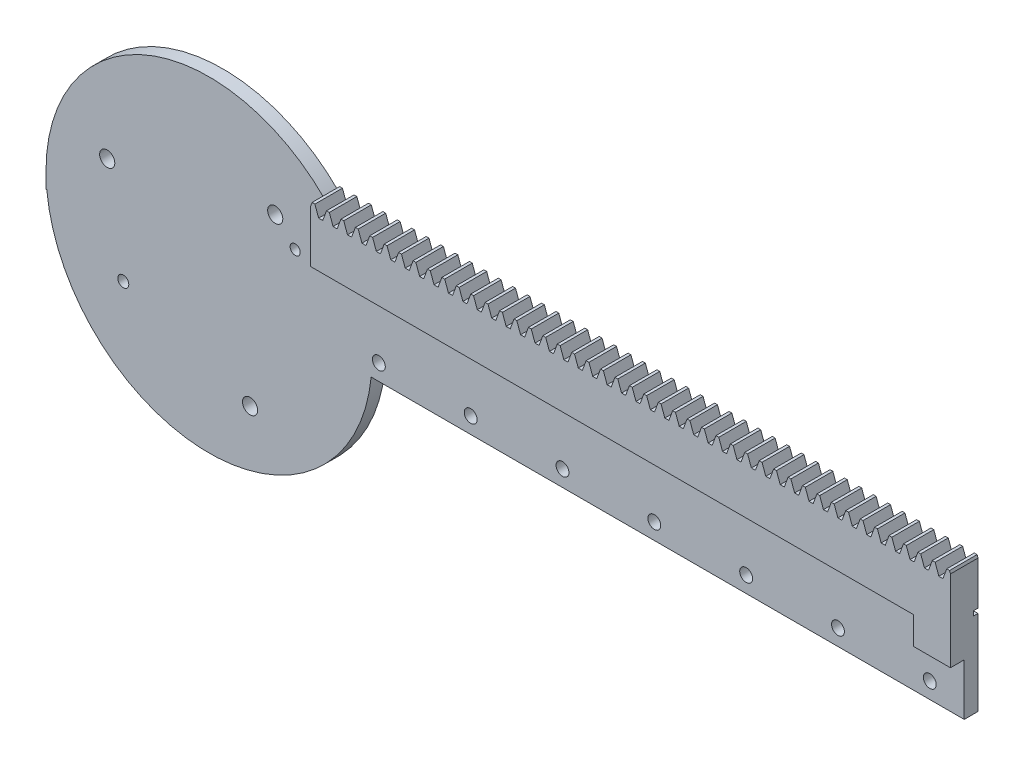
SolidWorks part; units mm, degrees
extrude "Blank" add sketch "BlankSke" against normal blind 3
sketch "BlankSke" plane through (0, 0, 0) normal (0, 0, 1) x (1, 0, 0)
  line L1 (0, 0) -> (200, 0)
  line L2 (0, 0) -> (0, 11)
  line L3 (0, 11) -> (200, 11)
  line L4 (200, 0) -> (200, 11)
  dimension "Length" = 200
  dimension "Blank_height" = 11
ref_plane "Plane1" through (0, 0, 0) normal (0, 0, 1) x (1, 0, 0)
ref_plane "Plane2" through (0, 0, 0) normal (0, 1, 0) x (1, 0, 0)
ref_plane "Plane3" through (0, 0, 0) normal (1, 0, 0) x (0, 0, -1)
other "Configuration Table"
sketch "HoldingSke" plane through (0, 0, 0) normal (0, 1, 0) x (1, 0, 0)
  line L0 (0, 0) -> (0.1392, 0.9903)
  line L1 (-15, 0) -> (100, 0) construction
  line L2 (0, 0) -> (-2.1039, 2.3779)
  line L3 (0, 0) -> (-11.863, 4.5341)
  line L4 (0, 0) -> (3.6497, 7.8269)
  line L5 (0, 0) -> (-23.7986, -8.8762)
  line L6 (0, 0) -> (-10.5278, -7.1032)
  line L9 (-71.009, 38.7566) -> (116.9296, 107.1606)
  line L10 (-76.2, 3.3779) -> (-66.2, 3.3779)
  line L11 (0, 0) -> (-3, 0)
  line L12 (-76.2, 101.6) -> (-76.162, 101.6)
  line L13 (24.9733, 27.94) -> (52.9518, 28.4284)
  line L14 (24.9733, 27.94) -> (24.9743, 27.94)
  line L15 (24.9733, 27.94) -> (100.4006, 29.5858)
  circle A0 centre (0, 0) radius 19.05
  circle A1 centre (0, 0) radius 5
  circle A2 centre (0, 0) radius 12.7
  dimension "MPH" = 10
  dimension "Diameter" = 38.1
  dimension "Num_teeth" = 65
  dimension "Pitch" = 1
  dimension "Show_teeth" = 998
  dimension "Thickness" = 12.7
  dimension "Ap" = 20
  dimension "Pitch_height" = 10
  dimension "Width" = 3
  dimension "Backlash" = 0.038
  dimension "Addendum_fac" = 1
  dimension "Dedendum_fac" = 1.25
  dimension "Clearance_fac" = 0.25
  dimension "Dedendum_add" = 0.001
  dimension "Length" = 200
  dimension "Module" = 1
sketch "TooCutSkeIll" plane through (0, 0, 0) normal (0, 0, 1) x (1, 0, 0)
  line L0 (-1.2538, 10.9737) -> (-0.5045, 8.9152)
  line L1 (-0.2687, 8.75) -> (0.2687, 8.75)
  line L2 (0.5045, 8.9152) -> (1.2538, 10.9737)
  line L3 (200, 11) -> (0, 11) construction
  line L4 (0, 0) -> (0, 64.897) construction
  line L5 (-13.208, 10) -> (12.954, 10) construction
  line L6 (0, 0) -> (200, 0) construction
  line L7 (0.8994, 10) -> (0.8994, 48.7463) construction
  line L8 (-0.8994, 10) -> (-0.8994, 48.7463) construction
  line L9 (1.2914, 11) -> (1.2914, 11.0254)
  line L10 (-1.2914, 11) -> (-1.2914, 11.0254)
  line L11 (-1.2914, 11.0254) -> (1.2914, 11.0254)
  arc A0 (0.2687, 8.75) -> (0.5045, 8.9152) centre (0.2687, 9.001) ccw
  arc A1 (-0.5045, 8.9152) -> (-0.2687, 8.75) centre (-0.2687, 9.001) ccw
  arc A2 (1.2914, 11) -> (1.2538, 10.9737) centre (1.2914, 10.96) ccw
  arc A3 (-1.2538, 10.9737) -> (-1.2914, 11) centre (-1.2914, 10.96) ccw
  dimension "Pitch_height" = 10
  dimension "Addendum_plus" = 1.0254
  dimension "Pressure_angle" = 20
  dimension "Gap_width" = 1.7988
  dimension "Dedendum" = 1.25
extrude "ToothCutIll" [suppressed] cut sketch "TooCutSkeIll" against normal through all
sketch "TooCutSkeSim" plane through (0, 0, 0) normal (0, 0, 1) x (1, 0, 0)
  line L0 (0.4444, 8.75) -> (-0.4444, 8.75)
  line L1 (1.2726, 11.0254) -> (0.4444, 8.75)
  line L2 (0, 17.4625) -> (0, 53.467) construction
  line L3 (1.2726, 11.0254) -> (-1.2726, 11.0254)
  line L6 (-1.2726, 11.0254) -> (-0.4444, 8.75)
  line L9 (-0.8994, 10) -> (0.8994, 10) construction
  line L10 (0, 0) -> (200, 0) construction
  line L11 (0.8994, 10) -> (0.8994, 53.467) construction
  line L12 (-0.8994, 10) -> (-0.8994, 53.467) construction
  dimension "Pitch_height" = 10
  dimension "Addendum_plus" = 1.0254
  dimension "Pressure_angle" = 20
  dimension "Gap_width" = 1.7988
  dimension "Dedendum" = 1.25
extrude "ToothCutSim" cut sketch "TooCutSkeSim" against normal through all
pattern_linear "TeethCuts" count 64 spacing 3.1416 along (1, 0, 0) of "ToothCutIll", "ToothCutSim"
sketch "草图5" plane through (0, 0, 0) normal (0, -1, 0) x (1, 0, 0)
  line L4 (200, 0) -> (0, 0)
  line L5 (0, 0) -> (0, -3)
  line L6 (0, -3) -> (200, -3)
  line L7 (200, -3) -> (200, 0)
  line L8 (200, 0) -> (0, 0)
  line L9 (0, 0) -> (0, -3)
  line L10 (0, -3) -> (200, -3)
  line L11 (200, -3) -> (200, 0)
  dimension "D1" = 0
extrude "凸台-拉伸3" add sketch "草图5" along normal blind 18.5
sketch "草图6" plane through (0, 0, -3) normal (0, 0, -1) x (-1, 0, 0)
  line L0 (0, 8.75) -> (0, -18.5) construction
  line L1 (0, -18.5) -> (-200, -18.5) construction
  circle A0 centre (-35.5, -15) radius 35.5
  dimension "D1" = 71
  dimension "D2" = 3.5
extrude "凸台-拉伸4" add sketch "草图6" against normal blind 3
sketch "草图7" plane through (0, 0, 0) normal (0, 0, 1) x (1, 0, 0)
  line L0 (200, 10.4466) -> (200, -1.25)
  line L1 (200, -18.5) -> (200, 10.4466) construction
  line L2 (200, -1.25) -> (60.6203, -1.25)
  line L5 (60.6203, 10.0842) -> (60.6203, -1.25)
  line L204 (70.827, -18.5) -> (200, -18.5)
  line L259 (200, -18.5) -> (200, 10.4466)
  line L260 (200, 10.4466) -> (199.7986, 11)
  line L261 (199.7986, 11) -> (199.1837, 11)
  line L262 (199.1837, 11) -> (198.3648, 8.75)
  line L263 (198.3648, 8.75) -> (197.4759, 8.75)
  line L264 (197.4759, 8.75) -> (196.657, 11)
  line L265 (196.657, 11) -> (196.0421, 11)
  line L266 (196.0421, 11) -> (195.2232, 8.75)
  line L267 (195.2232, 8.75) -> (194.3343, 8.75)
  line L268 (194.3343, 8.75) -> (193.5154, 11)
  line L269 (193.5154, 11) -> (192.9005, 11)
  line L270 (192.9005, 11) -> (192.0816, 8.75)
  line L271 (192.0816, 8.75) -> (191.1927, 8.75)
  line L272 (191.1927, 8.75) -> (190.3738, 11)
  line L273 (190.3738, 11) -> (189.7589, 11)
  line L274 (189.7589, 11) -> (188.94, 8.75)
  line L275 (188.94, 8.75) -> (188.0511, 8.75)
  line L276 (188.0511, 8.75) -> (187.2322, 11)
  line L277 (187.2322, 11) -> (186.6173, 11)
  line L278 (186.6173, 11) -> (185.7984, 8.75)
  line L279 (185.7984, 8.75) -> (184.9095, 8.75)
  line L280 (184.9095, 8.75) -> (184.0906, 11)
  line L281 (184.0906, 11) -> (183.4757, 11)
  line L282 (183.4757, 11) -> (182.6568, 8.75)
  line L283 (182.6568, 8.75) -> (181.7679, 8.75)
  line L284 (181.7679, 8.75) -> (180.949, 11)
  line L285 (180.949, 11) -> (180.3341, 11)
  line L286 (180.3341, 11) -> (179.5152, 8.75)
  line L287 (179.5152, 8.75) -> (178.6263, 8.75)
  line L288 (178.6263, 8.75) -> (177.8074, 11)
  line L289 (177.8074, 11) -> (177.1926, 11)
  line L290 (177.1926, 11) -> (176.3736, 8.75)
  line L291 (176.3736, 8.75) -> (175.4848, 8.75)
  line L292 (175.4848, 8.75) -> (174.6658, 11)
  line L293 (174.6658, 11) -> (174.051, 11)
  line L294 (174.051, 11) -> (173.232, 8.75)
  line L295 (173.232, 8.75) -> (172.3432, 8.75)
  line L296 (172.3432, 8.75) -> (171.5242, 11)
  line L297 (171.5242, 11) -> (170.9094, 11)
  line L298 (170.9094, 11) -> (170.0904, 8.75)
  line L299 (170.0904, 8.75) -> (169.2016, 8.75)
  line L300 (169.2016, 8.75) -> (168.3826, 11)
  line L301 (168.3826, 11) -> (167.7678, 11)
  line L302 (167.7678, 11) -> (166.9488, 8.75)
  line L303 (166.9488, 8.75) -> (166.06, 8.75)
  line L304 (166.06, 8.75) -> (165.241, 11)
  line L305 (165.241, 11) -> (164.6262, 11)
  line L306 (164.6262, 11) -> (163.8073, 8.75)
  line L307 (163.8073, 8.75) -> (162.9184, 8.75)
  line L308 (162.9184, 8.75) -> (162.0994, 11)
  line L309 (162.0994, 11) -> (161.4846, 11)
  line L310 (161.4846, 11) -> (160.6657, 8.75)
  line L311 (160.6657, 8.75) -> (159.7768, 8.75)
  line L312 (159.7768, 8.75) -> (158.9579, 11)
  line L313 (158.9579, 11) -> (158.343, 11)
  line L314 (158.343, 11) -> (157.5241, 8.75)
  line L315 (157.5241, 8.75) -> (156.6352, 8.75)
  line L316 (156.6352, 8.75) -> (155.8163, 11)
  line L317 (155.8163, 11) -> (155.2014, 11)
  line L318 (155.2014, 11) -> (154.3825, 8.75)
  line L319 (154.3825, 8.75) -> (153.4936, 8.75)
  line L320 (153.4936, 8.75) -> (152.6747, 11)
  line L321 (152.6747, 11) -> (152.0598, 11)
  line L322 (152.0598, 11) -> (151.2409, 8.75)
  line L323 (151.2409, 8.75) -> (150.352, 8.75)
  line L324 (150.352, 8.75) -> (149.5331, 11)
  line L325 (149.5331, 11) -> (148.9182, 11)
  line L326 (148.9182, 11) -> (148.0993, 8.75)
  line L327 (148.0993, 8.75) -> (147.2104, 8.75)
  line L328 (147.2104, 8.75) -> (146.3915, 11)
  line L329 (146.3915, 11) -> (145.7766, 11)
  line L330 (145.7766, 11) -> (144.9577, 8.75)
  line L331 (144.9577, 8.75) -> (144.0688, 8.75)
  line L332 (144.0688, 8.75) -> (143.2499, 11)
  line L333 (143.2499, 11) -> (142.635, 11)
  line L334 (142.635, 11) -> (141.8161, 8.75)
  line L335 (141.8161, 8.75) -> (140.9272, 8.75)
  line L336 (140.9272, 8.75) -> (140.1083, 11)
  line L337 (140.1083, 11) -> (139.4934, 11)
  line L338 (139.4934, 11) -> (138.6745, 8.75)
  line L339 (138.6745, 8.75) -> (137.7856, 8.75)
  line L340 (137.7856, 8.75) -> (136.9667, 11)
  line L341 (136.9667, 11) -> (136.3519, 11)
  line L342 (136.3519, 11) -> (135.5329, 8.75)
  line L343 (135.5329, 8.75) -> (134.644, 8.75)
  line L344 (134.644, 8.75) -> (133.8251, 11)
  line L345 (133.8251, 11) -> (133.2103, 11)
  line L346 (133.2103, 11) -> (132.3913, 8.75)
  line L347 (132.3913, 8.75) -> (131.5025, 8.75)
  line L348 (131.5025, 8.75) -> (130.6835, 11)
  line L349 (130.6835, 11) -> (130.0687, 11)
  line L350 (130.0687, 11) -> (129.2497, 8.75)
  line L351 (129.2497, 8.75) -> (128.3609, 8.75)
  line L352 (128.3609, 8.75) -> (127.5419, 11)
  line L353 (127.5419, 11) -> (126.9271, 11)
  line L354 (126.9271, 11) -> (126.1081, 8.75)
  line L355 (126.1081, 8.75) -> (125.2193, 8.75)
  line L356 (125.2193, 8.75) -> (124.4003, 11)
  line L357 (124.4003, 11) -> (123.7855, 11)
  line L358 (123.7855, 11) -> (122.9665, 8.75)
  line L359 (122.9665, 8.75) -> (122.0777, 8.75)
  line L360 (122.0777, 8.75) -> (121.2587, 11)
  line L361 (121.2587, 11) -> (120.6439, 11)
  line L362 (120.6439, 11) -> (119.825, 8.75)
  line L363 (119.825, 8.75) -> (118.9361, 8.75)
  line L364 (118.9361, 8.75) -> (118.1172, 11)
  line L365 (118.1172, 11) -> (117.5023, 11)
  line L366 (117.5023, 11) -> (116.6834, 8.75)
  line L367 (116.6834, 8.75) -> (115.7945, 8.75)
  line L368 (115.7945, 8.75) -> (114.9756, 11)
  line L369 (114.9756, 11) -> (114.3607, 11)
  line L370 (114.3607, 11) -> (113.5418, 8.75)
  line L371 (113.5418, 8.75) -> (112.6529, 8.75)
  line L372 (112.6529, 8.75) -> (111.834, 11)
  line L373 (111.834, 11) -> (111.2191, 11)
  line L374 (111.2191, 11) -> (110.4002, 8.75)
  line L375 (110.4002, 8.75) -> (109.5113, 8.75)
  line L376 (109.5113, 8.75) -> (108.6924, 11)
  line L377 (108.6924, 11) -> (108.0775, 11)
  line L378 (108.0775, 11) -> (107.2586, 8.75)
  line L379 (107.2586, 8.75) -> (106.3697, 8.75)
  line L380 (106.3697, 8.75) -> (105.5508, 11)
  line L381 (105.5508, 11) -> (104.9359, 11)
  line L382 (104.9359, 11) -> (104.117, 8.75)
  line L383 (104.117, 8.75) -> (103.2281, 8.75)
  line L384 (103.2281, 8.75) -> (102.4092, 11)
  line L385 (102.4092, 11) -> (101.7943, 11)
  line L386 (101.7943, 11) -> (100.9754, 8.75)
  line L387 (100.9754, 8.75) -> (100.0865, 8.75)
  line L388 (100.0865, 8.75) -> (99.2676, 11)
  line L389 (99.2676, 11) -> (98.6527, 11)
  line L390 (98.6527, 11) -> (97.8338, 8.75)
  line L391 (97.8338, 8.75) -> (96.9449, 8.75)
  line L392 (96.9449, 8.75) -> (96.126, 11)
  line L393 (96.126, 11) -> (95.5111, 11)
  line L394 (95.5111, 11) -> (94.6922, 8.75)
  line L395 (94.6922, 8.75) -> (93.8033, 8.75)
  line L396 (93.8033, 8.75) -> (92.9844, 11)
  line L397 (92.9844, 11) -> (92.3696, 11)
  line L398 (92.3696, 11) -> (91.5506, 8.75)
  line L399 (91.5506, 8.75) -> (90.6618, 8.75)
  line L400 (90.6618, 8.75) -> (89.8428, 11)
  line L401 (89.8428, 11) -> (89.228, 11)
  line L402 (89.228, 11) -> (88.409, 8.75)
  line L403 (88.409, 8.75) -> (87.5202, 8.75)
  line L404 (87.5202, 8.75) -> (86.7012, 11)
  line L405 (86.7012, 11) -> (86.0864, 11)
  line L406 (86.0864, 11) -> (85.2674, 8.75)
  line L407 (85.2674, 8.75) -> (84.3786, 8.75)
  line L408 (84.3786, 8.75) -> (83.5596, 11)
  line L409 (83.5596, 11) -> (82.9448, 11)
  line L410 (82.9448, 11) -> (82.1258, 8.75)
  line L411 (82.1258, 8.75) -> (81.237, 8.75)
  line L412 (81.237, 8.75) -> (80.418, 11)
  line L413 (80.418, 11) -> (79.8032, 11)
  line L414 (79.8032, 11) -> (78.9843, 8.75)
  line L415 (78.9843, 8.75) -> (78.0954, 8.75)
  line L416 (78.0954, 8.75) -> (77.2764, 11)
  line L417 (77.2764, 11) -> (76.6616, 11)
  line L418 (76.6616, 11) -> (75.8427, 8.75)
  line L419 (75.8427, 8.75) -> (74.9538, 8.75)
  line L420 (74.9538, 8.75) -> (74.1349, 11)
  line L421 (74.1349, 11) -> (73.52, 11)
  line L422 (73.52, 11) -> (72.7011, 8.75)
  line L423 (72.7011, 8.75) -> (71.8122, 8.75)
  line L424 (71.8122, 8.75) -> (70.9933, 11)
  line L425 (70.9933, 11) -> (70.3784, 11)
  line L426 (70.3784, 11) -> (69.5595, 8.75)
  line L427 (69.5595, 8.75) -> (68.6706, 8.75)
  line L428 (68.6706, 8.75) -> (67.8517, 11)
  line L429 (67.8517, 11) -> (67.2368, 11)
  line L430 (67.2368, 11) -> (66.4179, 8.75)
  line L431 (66.4179, 8.75) -> (65.529, 8.75)
  line L432 (65.529, 8.75) -> (64.7101, 11)
  line L433 (64.7101, 11) -> (64.0952, 11)
  line L434 (64.0952, 11) -> (63.2763, 8.75)
  line L435 (63.2763, 8.75) -> (62.3874, 8.75)
  line L436 (62.3874, 8.75) -> (61.5685, 11)
  line L437 (61.5685, 11) -> (60.9536, 11)
  line L438 (60.9536, 11) -> (60.6203, 10.0842)
  line L500 (11.3095, 10.9821) -> (11.303, 11)
  line L501 (11.303, 11) -> (10.6881, 11)
  line L502 (10.6881, 11) -> (10.3406, 10.045)
  line L503 (9.1146, 8.75) -> (8.9803, 8.75)
  line L504 (8.9803, 8.75) -> (8.1614, 11)
  line L505 (8.1614, 11) -> (7.5466, 11)
  line L506 (7.5466, 11) -> (6.7276, 8.75)
  line L507 (6.7276, 8.75) -> (5.8387, 8.75)
  line L508 (5.8387, 8.75) -> (5.0198, 11)
  line L509 (5.0198, 11) -> (4.405, 11)
  line L510 (4.405, 11) -> (3.586, 8.75)
  line L511 (3.586, 8.75) -> (2.6972, 8.75)
  line L512 (2.6972, 8.75) -> (1.8782, 11)
  line L513 (1.8782, 11) -> (1.2634, 11)
  line L514 (1.2634, 11) -> (0.4444, 8.75)
  line L515 (0.4444, 8.75) -> (0, 8.75)
  line L516 (0, 8.75) -> (0, -18.5)
  line L517 (0, -18.5) -> (0.173, -18.5)
  line L519 (200, 10.4466) -> (199.7986, 11)
  line L520 (199.7986, 11) -> (199.1837, 11)
  line L521 (199.1837, 11) -> (198.3648, 8.75)
  line L522 (198.3648, 8.75) -> (197.4759, 8.75)
  line L523 (197.4759, 8.75) -> (196.657, 11)
  line L524 (196.657, 11) -> (196.0421, 11)
  line L525 (196.0421, 11) -> (195.2232, 8.75)
  line L526 (195.2232, 8.75) -> (194.3343, 8.75)
  line L527 (194.3343, 8.75) -> (193.5154, 11)
  line L528 (193.5154, 11) -> (192.9005, 11)
  line L529 (192.9005, 11) -> (192.0816, 8.75)
  line L530 (192.0816, 8.75) -> (191.1927, 8.75)
  line L531 (191.1927, 8.75) -> (190.3738, 11)
  line L532 (190.3738, 11) -> (189.7589, 11)
  line L533 (189.7589, 11) -> (188.94, 8.75)
  line L534 (188.94, 8.75) -> (188.0511, 8.75)
  line L535 (188.0511, 8.75) -> (187.2322, 11)
  line L536 (187.2322, 11) -> (186.6173, 11)
  line L537 (186.6173, 11) -> (185.7984, 8.75)
  line L538 (185.7984, 8.75) -> (184.9095, 8.75)
  line L539 (184.9095, 8.75) -> (184.0906, 11)
  line L540 (184.0906, 11) -> (183.4757, 11)
  line L541 (183.4757, 11) -> (182.6568, 8.75)
  line L542 (182.6568, 8.75) -> (181.7679, 8.75)
  line L543 (181.7679, 8.75) -> (180.949, 11)
  line L544 (180.949, 11) -> (180.3341, 11)
  line L545 (180.3341, 11) -> (179.5152, 8.75)
  line L546 (179.5152, 8.75) -> (178.6263, 8.75)
  line L547 (178.6263, 8.75) -> (177.8074, 11)
  line L548 (177.8074, 11) -> (177.1926, 11)
  line L549 (177.1926, 11) -> (176.3736, 8.75)
  line L550 (176.3736, 8.75) -> (175.4848, 8.75)
  line L551 (175.4848, 8.75) -> (174.6658, 11)
  line L552 (174.6658, 11) -> (174.051, 11)
  line L553 (174.051, 11) -> (173.232, 8.75)
  line L554 (173.232, 8.75) -> (172.3432, 8.75)
  line L555 (172.3432, 8.75) -> (171.5242, 11)
  line L556 (171.5242, 11) -> (170.9094, 11)
  line L557 (170.9094, 11) -> (170.0904, 8.75)
  line L558 (170.0904, 8.75) -> (169.2016, 8.75)
  line L559 (169.2016, 8.75) -> (168.3826, 11)
  line L560 (168.3826, 11) -> (167.7678, 11)
  line L561 (167.7678, 11) -> (166.9488, 8.75)
  line L562 (166.9488, 8.75) -> (166.06, 8.75)
  line L563 (166.06, 8.75) -> (165.241, 11)
  line L564 (165.241, 11) -> (164.6262, 11)
  line L565 (164.6262, 11) -> (163.8073, 8.75)
  line L566 (163.8073, 8.75) -> (162.9184, 8.75)
  line L567 (162.9184, 8.75) -> (162.0994, 11)
  line L568 (162.0994, 11) -> (161.4846, 11)
  line L569 (161.4846, 11) -> (160.6657, 8.75)
  line L570 (160.6657, 8.75) -> (159.7768, 8.75)
  line L571 (159.7768, 8.75) -> (158.9579, 11)
  line L572 (158.9579, 11) -> (158.343, 11)
  line L573 (158.343, 11) -> (157.5241, 8.75)
  line L574 (157.5241, 8.75) -> (156.6352, 8.75)
  line L575 (156.6352, 8.75) -> (155.8163, 11)
  line L576 (155.8163, 11) -> (155.2014, 11)
  line L577 (155.2014, 11) -> (154.3825, 8.75)
  line L578 (154.3825, 8.75) -> (153.4936, 8.75)
  line L579 (153.4936, 8.75) -> (152.6747, 11)
  line L580 (152.6747, 11) -> (152.0598, 11)
  line L581 (152.0598, 11) -> (151.2409, 8.75)
  line L582 (151.2409, 8.75) -> (150.352, 8.75)
  line L583 (150.352, 8.75) -> (149.5331, 11)
  line L584 (149.5331, 11) -> (148.9182, 11)
  line L585 (148.9182, 11) -> (148.0993, 8.75)
  line L586 (148.0993, 8.75) -> (147.2104, 8.75)
  line L587 (147.2104, 8.75) -> (146.3915, 11)
  line L588 (146.3915, 11) -> (145.7766, 11)
  line L589 (145.7766, 11) -> (144.9577, 8.75)
  line L590 (144.9577, 8.75) -> (144.0688, 8.75)
  line L591 (144.0688, 8.75) -> (143.2499, 11)
  line L592 (143.2499, 11) -> (142.635, 11)
  line L593 (142.635, 11) -> (141.8161, 8.75)
  line L594 (141.8161, 8.75) -> (140.9272, 8.75)
  line L595 (140.9272, 8.75) -> (140.1083, 11)
  line L596 (140.1083, 11) -> (139.4934, 11)
  line L597 (139.4934, 11) -> (138.6745, 8.75)
  line L598 (138.6745, 8.75) -> (137.7856, 8.75)
  line L599 (137.7856, 8.75) -> (136.9667, 11)
  line L600 (136.9667, 11) -> (136.3519, 11)
  line L601 (136.3519, 11) -> (135.5329, 8.75)
  line L602 (135.5329, 8.75) -> (134.644, 8.75)
  line L603 (134.644, 8.75) -> (133.8251, 11)
  line L604 (133.8251, 11) -> (133.2103, 11)
  line L605 (133.2103, 11) -> (132.3913, 8.75)
  line L606 (132.3913, 8.75) -> (131.5025, 8.75)
  line L607 (131.5025, 8.75) -> (130.6835, 11)
  line L608 (130.6835, 11) -> (130.0687, 11)
  line L609 (130.0687, 11) -> (129.2497, 8.75)
  line L610 (129.2497, 8.75) -> (128.3609, 8.75)
  line L611 (128.3609, 8.75) -> (127.5419, 11)
  line L612 (127.5419, 11) -> (126.9271, 11)
  line L613 (126.9271, 11) -> (126.1081, 8.75)
  line L614 (126.1081, 8.75) -> (125.2193, 8.75)
  line L615 (125.2193, 8.75) -> (124.4003, 11)
  line L616 (124.4003, 11) -> (123.7855, 11)
  line L617 (123.7855, 11) -> (122.9665, 8.75)
  line L618 (122.9665, 8.75) -> (122.0777, 8.75)
  line L619 (122.0777, 8.75) -> (121.2587, 11)
  line L620 (121.2587, 11) -> (120.6439, 11)
  line L621 (120.6439, 11) -> (119.825, 8.75)
  line L622 (119.825, 8.75) -> (118.9361, 8.75)
  line L623 (118.9361, 8.75) -> (118.1172, 11)
  line L624 (118.1172, 11) -> (117.5023, 11)
  line L625 (117.5023, 11) -> (116.6834, 8.75)
  line L626 (116.6834, 8.75) -> (115.7945, 8.75)
  line L627 (115.7945, 8.75) -> (114.9756, 11)
  line L628 (114.9756, 11) -> (114.3607, 11)
  line L629 (114.3607, 11) -> (113.5418, 8.75)
  line L630 (113.5418, 8.75) -> (112.6529, 8.75)
  line L631 (112.6529, 8.75) -> (111.834, 11)
  line L632 (111.834, 11) -> (111.2191, 11)
  line L633 (111.2191, 11) -> (110.4002, 8.75)
  line L634 (110.4002, 8.75) -> (109.5113, 8.75)
  line L635 (109.5113, 8.75) -> (108.6924, 11)
  line L636 (108.6924, 11) -> (108.0775, 11)
  line L637 (108.0775, 11) -> (107.2586, 8.75)
  line L638 (107.2586, 8.75) -> (106.3697, 8.75)
  line L639 (106.3697, 8.75) -> (105.5508, 11)
  line L640 (105.5508, 11) -> (104.9359, 11)
  line L641 (104.9359, 11) -> (104.117, 8.75)
  line L642 (104.117, 8.75) -> (103.2281, 8.75)
  line L643 (103.2281, 8.75) -> (102.4092, 11)
  line L644 (102.4092, 11) -> (101.7943, 11)
  line L645 (101.7943, 11) -> (100.9754, 8.75)
  line L646 (100.9754, 8.75) -> (100.0865, 8.75)
  line L647 (100.0865, 8.75) -> (99.2676, 11)
  line L648 (99.2676, 11) -> (98.6527, 11)
  line L649 (98.6527, 11) -> (97.8338, 8.75)
  line L650 (97.8338, 8.75) -> (96.9449, 8.75)
  line L651 (96.9449, 8.75) -> (96.126, 11)
  line L652 (96.126, 11) -> (95.5111, 11)
  line L653 (95.5111, 11) -> (94.6922, 8.75)
  line L654 (94.6922, 8.75) -> (93.8033, 8.75)
  line L655 (93.8033, 8.75) -> (92.9844, 11)
  line L656 (92.9844, 11) -> (92.3696, 11)
  line L657 (92.3696, 11) -> (91.5506, 8.75)
  line L658 (91.5506, 8.75) -> (90.6618, 8.75)
  line L659 (90.6618, 8.75) -> (89.8428, 11)
  line L660 (89.8428, 11) -> (89.228, 11)
  line L661 (89.228, 11) -> (88.409, 8.75)
  line L662 (88.409, 8.75) -> (87.5202, 8.75)
  line L663 (87.5202, 8.75) -> (86.7012, 11)
  line L664 (86.7012, 11) -> (86.0864, 11)
  line L665 (86.0864, 11) -> (85.2674, 8.75)
  line L666 (85.2674, 8.75) -> (84.3786, 8.75)
  line L667 (84.3786, 8.75) -> (83.5596, 11)
  line L668 (83.5596, 11) -> (82.9448, 11)
  line L669 (82.9448, 11) -> (82.1258, 8.75)
  line L670 (82.1258, 8.75) -> (81.237, 8.75)
  line L671 (81.237, 8.75) -> (80.418, 11)
  line L672 (80.418, 11) -> (79.8032, 11)
  line L673 (79.8032, 11) -> (78.9843, 8.75)
  line L674 (78.9843, 8.75) -> (78.0954, 8.75)
  line L675 (78.0954, 8.75) -> (77.2764, 11)
  line L676 (77.2764, 11) -> (76.6616, 11)
  line L677 (76.6616, 11) -> (75.8427, 8.75)
  line L678 (75.8427, 8.75) -> (74.9538, 8.75)
  line L679 (74.9538, 8.75) -> (74.1349, 11)
  line L680 (74.1349, 11) -> (73.52, 11)
  line L681 (73.52, 11) -> (72.7011, 8.75)
  line L682 (72.7011, 8.75) -> (71.8122, 8.75)
  line L683 (71.8122, 8.75) -> (70.9933, 11)
  line L684 (70.9933, 11) -> (70.3784, 11)
  line L685 (70.3784, 11) -> (69.5595, 8.75)
  line L686 (69.5595, 8.75) -> (68.6706, 8.75)
  line L687 (68.6706, 8.75) -> (67.8517, 11)
  line L688 (67.8517, 11) -> (67.2368, 11)
  line L689 (67.2368, 11) -> (66.4179, 8.75)
  line L690 (66.4179, 8.75) -> (65.529, 8.75)
  line L691 (65.529, 8.75) -> (64.7101, 11)
  line L692 (64.7101, 11) -> (64.0952, 11)
  line L693 (64.0952, 11) -> (63.2763, 8.75)
  line L694 (63.2763, 8.75) -> (62.3874, 8.75)
  line L695 (62.3874, 8.75) -> (61.5685, 11)
  line L696 (61.5685, 11) -> (60.9536, 11)
  line L697 (60.9536, 11) -> (60.6203, 10.0842)
  arc A3 (0.173, -18.5) -> (70.827, -18.5) centre (35.5, -15) ccw
  arc A5 (60.6203, 10.0842) -> (11.3095, 10.9821) centre (35.5, -15) ccw
  arc A7 (10.3406, 10.045) -> (9.1146, 8.75) centre (35.5, -15) ccw
  dimension "D1" = 0
extrude "凸台-拉伸6" add sketch "草图7" along normal blind 3
sketch "草图8" plane through (0, 0, 0) normal (0, 0, 1) x (1, 0, 0)
  line L0 (35.5, 20.5) -> (0, 20.5)
  line L2 (0, 8.75) -> (0, -18.5) construction
  line L3 (0, -15) -> (0, 20.5)
  arc A0 (35.5, 20.5) -> (0, -15) centre (35.5, -15) ccw
extrude "切除-拉伸1" cut sketch "草图8" against normal blind 3
sketch "草图9" plane through (0, 0, 0) normal (0, 0, 1) x (1, 0, 0)
  circle A0 centre (72.5, -15) radius 1.4
  circle A1 centre (92.5, -15) radius 1.4
  circle A2 centre (112.5, -15) radius 1.4
  circle A3 centre (132.5, -15) radius 1.4
  circle A4 centre (152.5, -15) radius 1.4
  circle A5 centre (172.5, -15) radius 1.4
  circle A6 centre (192.5, -15) radius 1.4
  dimension "D1" = 2.8
  dimension "D2" = 7
extrude "切除-拉伸2" cut sketch "草图9" against normal blind 10
sketch "草图11" plane through (0, 0, 0) normal (0, 0, 1) x (1, 0, 0)
  line L1 (200, -1.25) -> (192, -1.25)
  line L2 (200, -1.25) -> (200, -7.25)
  line L3 (200, -7.25) -> (192, -7.25)
  line L4 (192, -1.25) -> (192, -7.25)
  dimension "D1" = 8
  dimension "D2" = 6
extrude "凸台-拉伸7" add sketch "草图11" along normal blind 3
sketch "草图12" plane through (0, 0, -3) normal (0, 0, -1) x (-1, 0, 0)
  line L0 (-200, -18.5) -> (-200, 10.4466) construction
  line L1 (-200, 1) -> (-70.8357, 1)
  line L2 (-200, 1) -> (-200, 0)
  line L3 (-200, 0) -> (-70.8357, 0)
  line L4 (-70.8357, 1) -> (-70.8357, 0)
  dimension "D1" = 1
extrude "切除-拉伸3" cut sketch "草图12" against normal blind 1
sketch "草图13" plane through (0, 0, -3) normal (0, 0, -1) x (-1, 0, 0)
  circle A1 centre (-13.3322, -6.0551) radius 1.65
  circle A3 centre (-49.925, 1.6877) radius 1.65
  circle A4 centre (-44.4449, -37.1678) radius 1.65
  circle A6 centre (-54.2801, -2.7253) radius 1.1
  circle A7 centre (-16.8324, -27.4451) radius 1.2
  dimension "D1" = 2.2
  dimension "D2" = 3.3
  dimension "D4" = 3.3
  dimension "D5" = 3.3
extrude "切除-拉伸4" cut sketch "草图13" against normal through all
equation "' \"Module@HoldingSke\" = 6.35"
equation "' \"Num_teeth@HoldingSke\" = 12"
equation "' \"Ap@HoldingSke\" =  20"
equation "' \"Ap@HoldingSke\" = 20"
equation "' \"Width@HoldingSke\" = 0.25 * 25.4"
equation "' \"Show_teeth@HoldingSke\" = 500"
equation "' \"Backlash@HoldingSke\" = 0.009 * 25.4"
equation "' \"Addendum_fac@HoldingSke\" = 1.0"
equation "' \"Dedendum_fac@HoldingSke\" = 1.25"
equation "' \"Dedendum_add@HoldingSke\" = 0.00005 * 25.4"
equation "' \"Clearance_fac@HoldingSke\" = 0.25"
equation "' \"Pitch_height@HoldingSke\" = 1 * 25.4"
equation "' \"Length@HoldingSke\" = 4.71 * 25.4"
equation "\"Pitch@HoldingSke\" = 1 / \"Module@HoldingSke\""
equation "\"MPH@HoldingSke\" = \"Dedendum_fac@HoldingSke\" / \"Pitch@HoldingSke\" + 2 * \"Dedendum_add@HoldingSke\" + 0.002 * 25.4"
equation "\"MPH@HoldingSke\" = ((sgn( \"MPH@HoldingSke\" - \"Pitch_height@HoldingSke\")+1)*( \"MPH@HoldingSke\" - \"Pitch_height@HoldingSke\"))/2 + \"Pitch_height@HoldingSke\""
equation "\"Blank_height@BlankSke\" = \"Pitch_height@HoldingSke\" + \"Addendum_fac@HoldingSke\"  / \"Pitch@HoldingSke\" "
equation "\"Length@BlankSke\" =  \"Length@HoldingSke\""
equation "\"Face_width@Blank\" = \"Width@HoldingSke\""
equation "\"Pressure_angle@TooCutSkeIll\" = \"Ap@HoldingSke\""
equation "\"Addendum_plus@TooCutSkeIll\" =  \"Addendum_fac@HoldingSke\"  / \"Pitch@HoldingSke\" + 0.001 *25.4"
equation "\"Dedendum@TooCutSkeIll\" = \"Dedendum_fac@HoldingSke\"  / \"Pitch@HoldingSke\""
equation "\"Pitch_height@TooCutSkeIll\" =  \"MPH@HoldingSke\""
equation "\"Gap_width@TooCutSkeIll\" = 3.14159265 / 2 / \"Pitch@HoldingSke\" + 6 * \"Backlash@HoldingSke\""
equation "\"Pressure_angle@TooCutSkeSim\" = \"Ap@HoldingSke\""
equation "\"Addendum_plus@TooCutSkeSim\" =  \"Addendum_fac@HoldingSke\"  / \"Pitch@HoldingSke\" + 0.001 * 25.4"
equation "\"Dedendum@TooCutSkeSim\" = \"Dedendum_fac@HoldingSke\"  / \"Pitch@HoldingSke\""
equation "\"Pitch_height@TooCutSkeSim\" =  \"MPH@HoldingSke\""
equation "\"Gap_width@TooCutSkeSim\" = 3.14159265 / 2 / \"Pitch@HoldingSke\" + 6 * \"Backlash@HoldingSke\""
equation "\"Root_fillet@TooCutSkeIll\" = \"Clearance_fac@HoldingSke\" / \"Pitch@HoldingSke\" + \"Dedendum_add@HoldingSke\""
equation "\"Break_rad@TooCutSkeIll\" = 0.02 / \"Pitch@HoldingSke\" * 2"
equation "\"Linear_pitch@TeethCuts\" = 3.14159265 / \"Pitch@HoldingSke\""
equation "\"Num_teeth@HoldingSke\" = int( ( \"Length@HoldingSke\" + 0 ) / (3.14159265 / \"Pitch@HoldingSke\")) + 0.9999  + 1"
equation " \"Num_teeth@TeethCuts\" = int( \"Show_teeth@HoldingSke\" ) + 1"
equation " \"Num_teeth@TeethCuts\" = ((sgn( \"Num_teeth@TeethCuts\" - \"Num_teeth@HoldingSke\" )-1)*( \"Num_teeth@TeethCuts\" - \"Num_teeth@HoldingSke\" ))/-2+ \"Num_teeth@HoldingSke\""
equation " \"Num_teeth@TeethCuts\" = ((sgn( \"Num_teeth@TeethCuts\" - 2.0)+1)*( \"Num_teeth@TeethCuts\" - 2.0))/2 +2.0"
